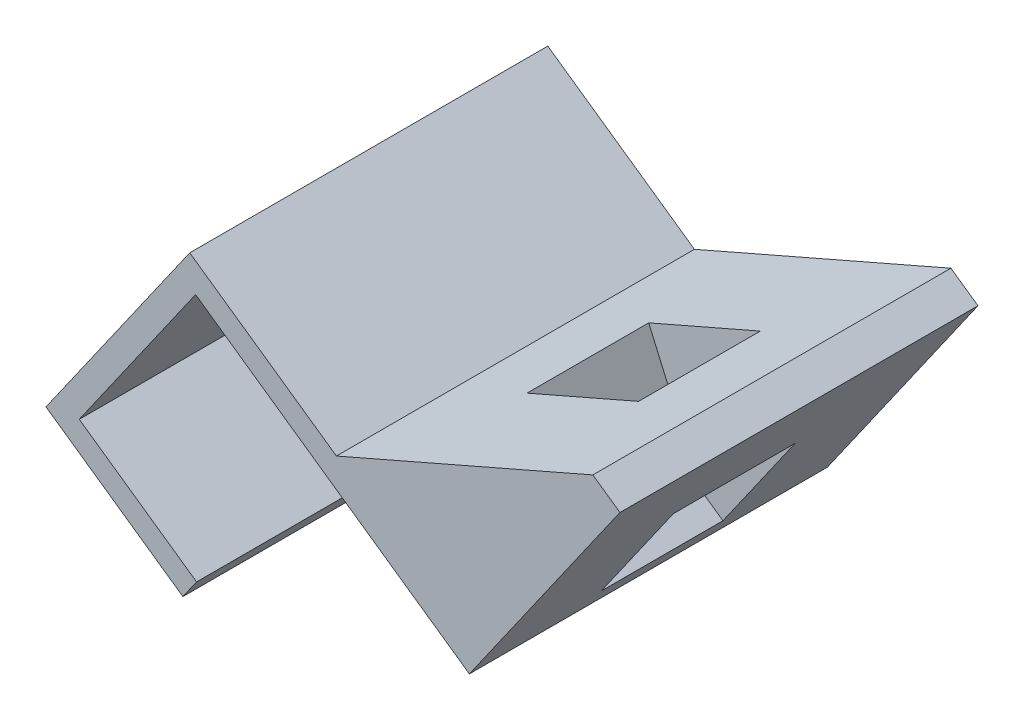
SolidWorks part; units mm, degrees
ref_plane "Front Plane" through (0, 0, 0) normal (0, 0, 1) x (1, 0, 0)
ref_plane "Top Plane" through (0, 0, 0) normal (0, 1, 0) x (1, 0, 0)
ref_plane "Right Plane" through (0, 0, 0) normal (1, 0, 0) x (0, 0, -1)
sketch "Sketch1" plane through (0, 0, 0) normal (0, 0, 1) x (1, 0, 0)
  line L0 (-71.0845, 0) -> (65.5432, 0) construction
  line L1 (-71.0845, 0) -> (-55.7903, 21.8489)
  line L2 (-55.7903, 21.8489) -> (-24.5775, 0)
  line L3 (-71.0845, 0) -> (-56.5186, -10.1962)
  dimension "D1" = 38.1
  dimension "D2" = 26.67
  dimension "D3" = 17.78
extrude "Extrude-Thin1" add sketch "Sketch1" along normal mid plane 38.1 thin
sketch "Sketch8" plane through (-16.495, 11.5465, 0) normal (0.8192, -0.5735, 0) x (0.5735, 0.8192, 0)
  line L1 (-14.0943, 19.05) -> (11.3057, 19.05)
  line L2 (-14.0943, 19.05) -> (-14.0943, -19.05)
  line L3 (-14.0943, -19.05) -> (11.3057, -19.05)
  line L4 (11.3057, 19.05) -> (11.3057, -19.05)
  dimension "D1" = 38.1
  dimension "D2" = 25.4
extrude "Boss-Extrude1" add sketch "Sketch8" against normal blind 19.05
sketch "Sketch12" plane through (0, 0, -19.05) normal (0, 0, -1) x (-1, 0, 0)
  line L7 (40.1839, 10.9245) -> (24.5775, 0) construction
  line L8 (10.0116, 20.8085) -> (26.0341, -2.0808) construction
  line L9 (25.618, 31.7329) -> (10.0116, 20.8085) construction
  line L10 (40.1839, 10.9245) -> (12.8958, 22.8274)
  line L11 (12.8958, 22.8274) -> (25.618, 31.7329)
  line L12 (25.618, 31.7329) -> (40.1839, 10.9245)
  dimension "D1" = 31.441
extrude "Cut-Extrude3" cut sketch "Sketch12" against normal through all both and the other way through all
sketch "Sketch13" plane through (-10.427, 23.9043, 0) normal (-0.3998, 0.9166, 0) x (0.9166, 0.3998, 0)
  line L0 (-32.4646, 0) -> (-2.6935, 0) construction
  line L1 (-32.4646, -19.05) -> (-32.4646, 19.05) construction
  line L2 (-2.6935, -19.05) -> (-2.6935, 19.05) construction
  line L3 (-17.579, -19.05) -> (-17.579, 19.05) construction
  line L4 (-2.6935, -19.05) -> (-32.4646, -19.05) construction
  line L5 (-2.6935, 19.05) -> (-32.4646, 19.05) construction
  line L7 (-11.102, -6.477) -> (-24.056, -6.477)
  line L8 (-11.102, -6.477) -> (-11.102, 6.477)
  line L9 (-11.102, 6.477) -> (-24.056, 6.477)
  line L10 (-24.056, -6.477) -> (-24.056, 6.477)
  line L11 (-11.102, -6.477) -> (-24.056, 6.477) construction
  line L12 (-11.102, 6.477) -> (-24.056, -6.477) construction
  point P12 (-17.579, 0)
  dimension "D1" = 12.954
  dimension "D2" = 12.954
extrude "Cut-Extrude4" cut sketch "Sketch13" against normal offset from surface 2.54 and the other way through all up to face at (-40.6001, 8.1153, 0)
